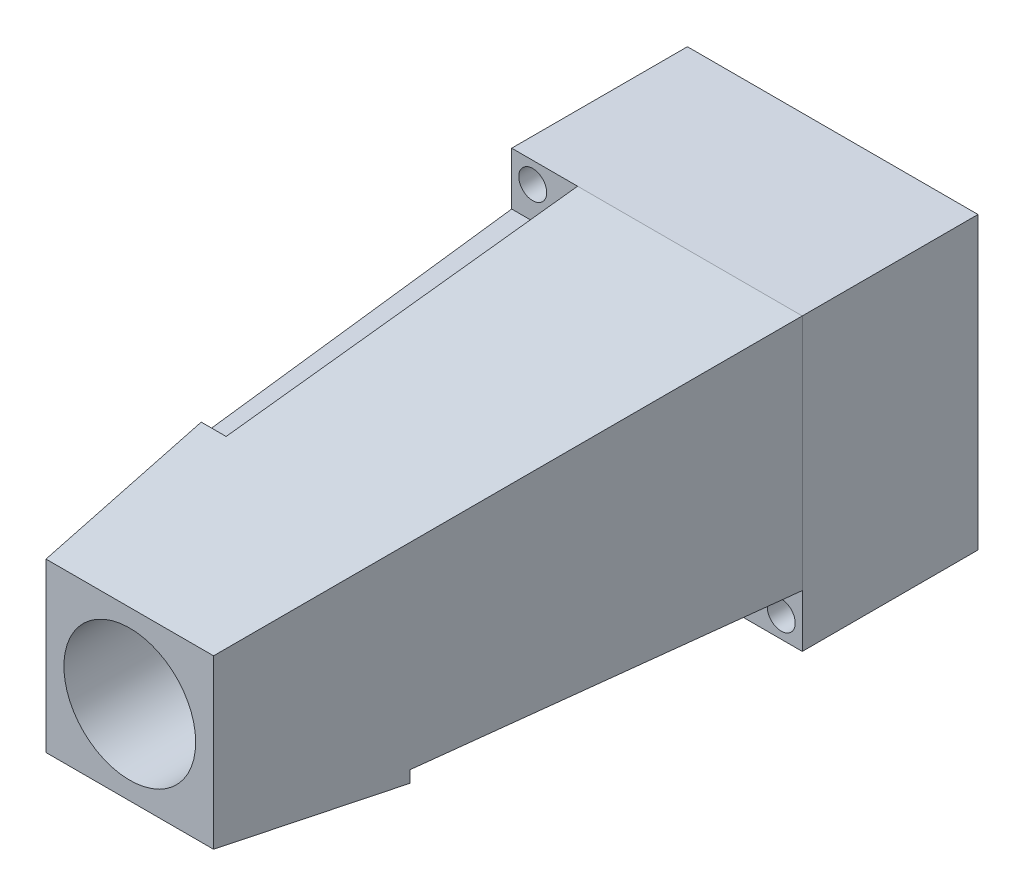
SolidWorks part; units mm, degrees
ref_plane "Front" through (0, 0, 0) normal (0, 0, 1) x (1, 0, 0)
ref_plane "Top" through (0, 0, 0) normal (0, 1, 0) x (1, 0, 0)
ref_plane "Right" through (0, 0, 0) normal (1, 0, 0) x (0, 0, -1)
sketch "Sketch1" plane through (0, 0, 0) normal (0, 0, 1) x (1, 0, 0)
  line L0 (8.6584, -67.7619) -> (8.6584, -101.7619) construction
  line L1 (8.6584, -102.7619) -> (-33.3416, -102.7619)
  line L2 (8.6584, -102.7619) -> (8.6584, -60.7619)
  line L3 (8.6584, -60.7619) -> (-33.3416, -60.7619)
  line L4 (-33.3416, -102.7619) -> (-33.3416, -60.7619)
  line L5 (7.6584, -102.7619) -> (-26.3416, -102.7619) construction
  line L6 (-25.0416, -94.4619) -> (-25.0416, -69.0619)
  line L7 (-32.3416, -60.7619) -> (1.6584, -60.7619) construction
  line L8 (0.3584, -69.0619) -> (-25.0416, -69.0619)
  line L9 (0.3584, -94.4619) -> (0.3584, -69.0619)
  line L10 (0.3584, -94.4619) -> (-25.0416, -94.4619)
  line L11 (-33.3416, -125.6219) -> (-33.3416, -63.3019) construction
  circle A0 centre (-12.3416, -81.7619) radius 9.525
  circle A1 centre (-30.3021, -63.8014) radius 2.0193
  circle A2 centre (-30.3021, -63.8014) radius 2.0193 construction
  circle A3 centre (5.6189, -99.7224) radius 2.0193
  circle A4 centre (5.6189, -99.7224) radius 2.0193 construction
  point P0 (0, 0)
  point P21 (-25.0416, -81.7619)
  point P23 (-12.3416, -69.0619)
  point P31 (8.6584, -81.7619)
  point P32 (-12.3416, -60.7619)
  dimension "D2" = 19.05
  dimension "D3" = 25.4
  dimension "D1" = 25.4
extrude "Boss-Extrude2" add sketch "Sketch1" along normal blind 25.4
ref_plane "Plane1" through (0, 0, 101.6) normal (0, 0, 1) x (1, 0, 0)
sketch "Sketch14" plane through (0, 0, 101.6) normal (0, 0, 1) x (1, 0, 0)
  line L15 (-0.2316, -93.8719) -> (-0.2316, -69.6519)
  line L16 (-0.2316, -69.6519) -> (-24.4516, -69.6519)
  line L17 (-24.4516, -93.8719) -> (-24.4516, -69.6519)
  line L18 (-0.2316, -93.8719) -> (-24.4516, -93.8719)
sketch "Sketch16" plane through (0, 0, 25.4) normal (0, 0, 1) x (1, 0, 0)
  line L0 (-33.3416, -102.7619) -> (-33.3416, -60.7619) construction
  line L1 (8.6584, -102.7619) -> (-33.3416, -102.7619) construction
  line L2 (8.6584, -60.7619) -> (-33.3416, -60.7619) construction
  line L3 (8.6584, -102.7619) -> (8.6584, -60.7619) construction
  line L4 (-33.3416, -102.7619) -> (-33.3416, -60.7619)
  line L5 (8.6584, -102.7619) -> (-33.3416, -102.7619)
  line L6 (8.6584, -60.7619) -> (-33.3416, -60.7619)
  line L7 (8.6584, -102.7619) -> (8.6584, -60.7619)
loft "Loft3" add profiles "Sketch16", "Sketch14"
sketch "Sketch17" plane through (0, 0, 101.6) normal (0, 0, 1) x (1, 0, 0)
  line L0 (-0.2316, -93.8719) -> (-0.2316, -69.6519) construction
  line L1 (-24.4516, -93.8719) -> (-0.2316, -93.8719) construction
  circle A0 centre (-12.3416, -81.7619) radius 9.525
  point P5 (-0.2316, -81.7619)
  point P8 (-12.3416, -93.8719)
  dimension "D1" = 19.05
extrude "Cut-Extrude11" cut sketch "Sketch17" against normal through all
sketch "Sketch18" plane through (0, -60.7619, 0) normal (0, 1, 0) x (1, 0, 0)
  line L0 (8.6584, -25.4) -> (-33.3416, -25.4) construction
  line L1 (-23.8166, -25.4) -> (-42.8666, -25.4)
  line L2 (-23.8166, -25.4) -> (-23.8166, -76.2)
  line L3 (-23.8166, -76.2) -> (-42.8666, -76.2)
  line L4 (-42.8666, -25.4) -> (-42.8666, -76.2)
  line L5 (-33.3416, -25.4) -> (-33.3416, 0) construction
  point P6 (-33.3416, -25.4)
  dimension "D1" = 50.8
  dimension "D2" = 19.05
extrude "Cut-Extrude16" cut sketch "Sketch18" against normal blind 7.62
sketch "Sketch19" plane through (0, -102.7619, 0) normal (0, -1, 0) x (1, 0, 0)
  line L0 (8.6584, 25.4) -> (-33.3416, 25.4) construction
  line L1 (-0.8666, 25.4) -> (18.1834, 25.4)
  line L2 (-0.8666, 25.4) -> (-0.8666, 76.2)
  line L3 (-0.8666, 76.2) -> (18.1834, 76.2)
  line L4 (18.1834, 25.4) -> (18.1834, 76.2)
  line L5 (8.6584, 25.4) -> (8.6584, 0) construction
  point P8 (8.6584, 25.4)
  dimension "D1" = 50.8
  dimension "D2" = 19.05
extrude "Cut-Extrude17" cut sketch "Sketch19" against normal blind 7.62
